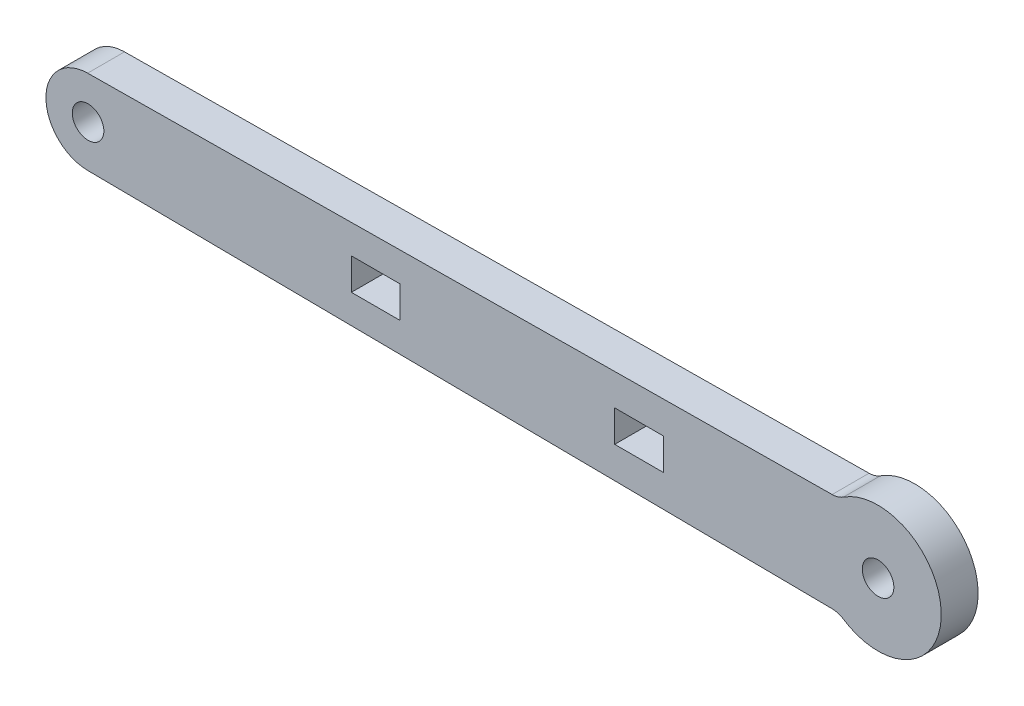
SolidWorks part; units mm, degrees
material "Balsa"
ref_plane "Front Plane" through (0, 0, 0) normal (0, 0, 1) x (1, 0, 0)
ref_plane "Top Plane" through (0, 0, 0) normal (0, 1, 0) x (1, 0, 0)
ref_plane "Right Plane" through (0, 0, 0) normal (1, 0, 0) x (0, 0, -1)
sketch "Sketch1" plane through (0, 0, 0) normal (0, 0, 1) x (1, 0, 0)
  line L0 (0, 0) -> (-75, 0) construction
  line L1 (-75.0394, 3.9998) -> (-3.7258, 4.7031)
  line L2 (-75.0394, -3.9998) -> (-3.7258, -4.7031)
  line L14 (-45.3649, -1.5) -> (-45.3649, 1.5)
  line L16 (-50, 1.5) -> (-50, -1.5)
  line L19 (-25, -1.5) -> (-25, 1.5)
  line L20 (-50, -1.5) -> (-45.3649, -1.5)
  line L21 (-50, -1.5) -> (-50, 1.5)
  line L22 (-50, 1.5) -> (-45.3649, 1.5)
  line L23 (-45.3649, -1.5) -> (-45.3649, 1.5)
  line L24 (-25, -1.5) -> (-20.3649, -1.5)
  line L25 (-20.3649, -1.5) -> (-20.3649, 1.5)
  line L26 (-25, 1.5) -> (-20.3649, 1.5)
  circle A0 centre (-75, 0) radius 1.5
  circle A1 centre (0, 0) radius 1.5
  arc A2 (-75.0394, 3.9998) -> (-75.0394, -3.9998) centre (-75, 0) ccw
  arc A3 (-3.7258, -4.7031) -> (-3.7258, 4.7031) centre (0, 0) ccw
  dimension "D2" = 3
  dimension "D3" = 12
  dimension "D4" = 4
  dimension "D1" = 75
  dimension "D5" = 1.13
  dimension "D6" = 25
  dimension "D7" = 4.6351
  dimension "D8" = 3
  dimension "D9" = 2
extrude "Boss-Extrude1" add sketch "Sketch1" along normal blind 3.5
fillet "Fillet1" radius 2 2 edges at (-3.7258, -4.7031, 1.75) (-3.7258, 4.7031, 1.75)
